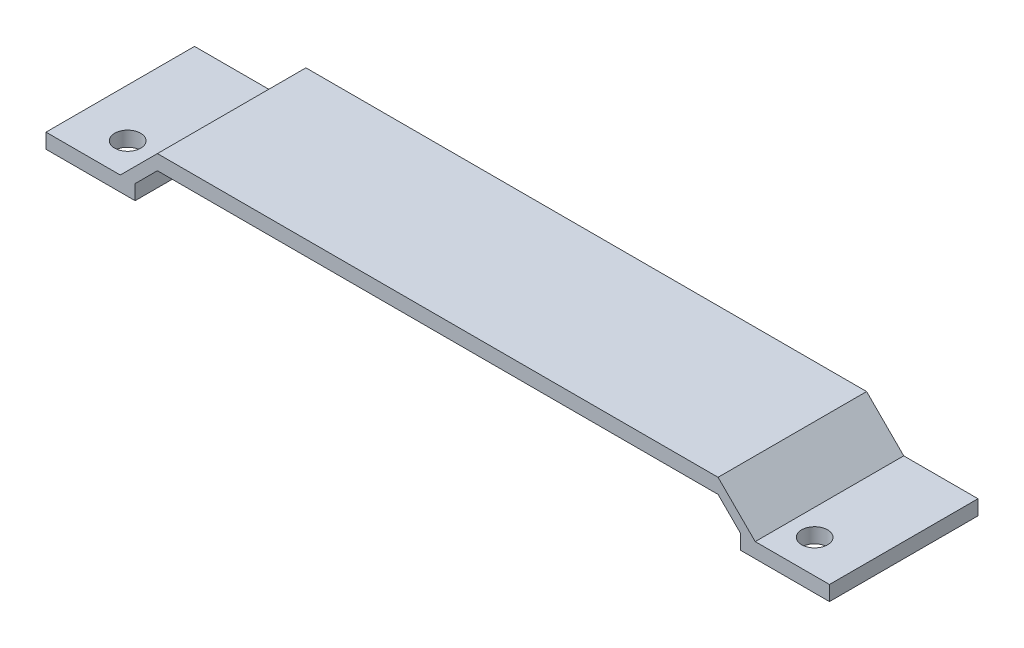
SolidWorks part; units mm, degrees
ref_plane "Plan de face" through (0, 0, 0) normal (0, 0, 1) x (1, 0, 0)
ref_plane "Plan de dessus" through (0, 0, 0) normal (0, 1, 0) x (1, 0, 0)
ref_plane "Plan de droite" through (0, 0, 0) normal (1, 0, 0) x (0, 0, -1)
sketch "Esquisse4" plane through (0, 0, 0) normal (0, 0, 1) x (1, 0, 0)
  line L0 (0, 0) -> (0, 2)
  line L5 (37.75, 0) -> (-37.75, 0)
  line L6 (37.75, 2) -> (-37.75, 2)
  line L15 (-37.75, 0) -> (-37.75, 2)
  line L16 (-40.75, -3) -> (-52.75, -3)
  line L17 (-40.75, -3) -> (-40.75, -5)
  line L18 (-52.75, -3) -> (-52.75, -5)
  line L19 (-40.75, -5) -> (-52.75, -5)
  line L20 (-40.75, -3) -> (-37.75, 0)
  line L21 (-37.75, 2) -> (-42.75, -3)
  line L22 (37.75, 2) -> (42.75, -3)
  line L23 (40.75, -3) -> (37.75, 0)
  line L24 (40.75, -5) -> (52.75, -5)
  line L25 (52.75, -3) -> (52.75, -5)
  line L26 (40.75, -3) -> (40.75, -5)
  line L27 (40.75, -3) -> (52.75, -3)
  line L28 (37.75, 0) -> (37.75, 2)
  point P5 (-24.2505, -5.3276)
  dimension "D1" = 2
  dimension "D2" = 12
  dimension "D3" = 45
  dimension "D4" = 105.5
  dimension "D5" = 3
extrude "Boss.-Extru.2" add sketch "Esquisse4" along normal blind 20 contours L19 L17 L16 L18 | L15 L21 L16 L20 | L15 L5 L0 L6 | L5 L28 L6 L0 | L28 L23 L27 L22 | L27 L26 L24 L25
sketch "Esquisse5" plane through (0, 2, 0) normal (0, 1, 0) x (1, 0, 0)
  line L0 (0, 0) -> (0, -20) construction
  line L1 (37.75, 0) -> (-37.75, 0) construction
  line L2 (37.75, -20) -> (-37.75, -20) construction
  line L3 (0, -10) -> (37.75, -10) construction
  line L4 (37.75, -20) -> (37.75, 0) construction
  line L5 (-42.75, -20) -> (-52.75, -20) construction
  line L6 (-52.75, -20) -> (-52.75, 0) construction
  circle A2 centre (-46.25, -15.5) radius 1.75
  circle A4 centre (46.25, -15.5) radius 1.75
  dimension "D2" = 3.5
  dimension "D1" = 4.5
  dimension "D3" = 6.5
extrude "Enlèv. mat.-Extru.1" cut sketch "Esquisse5" against normal through all
